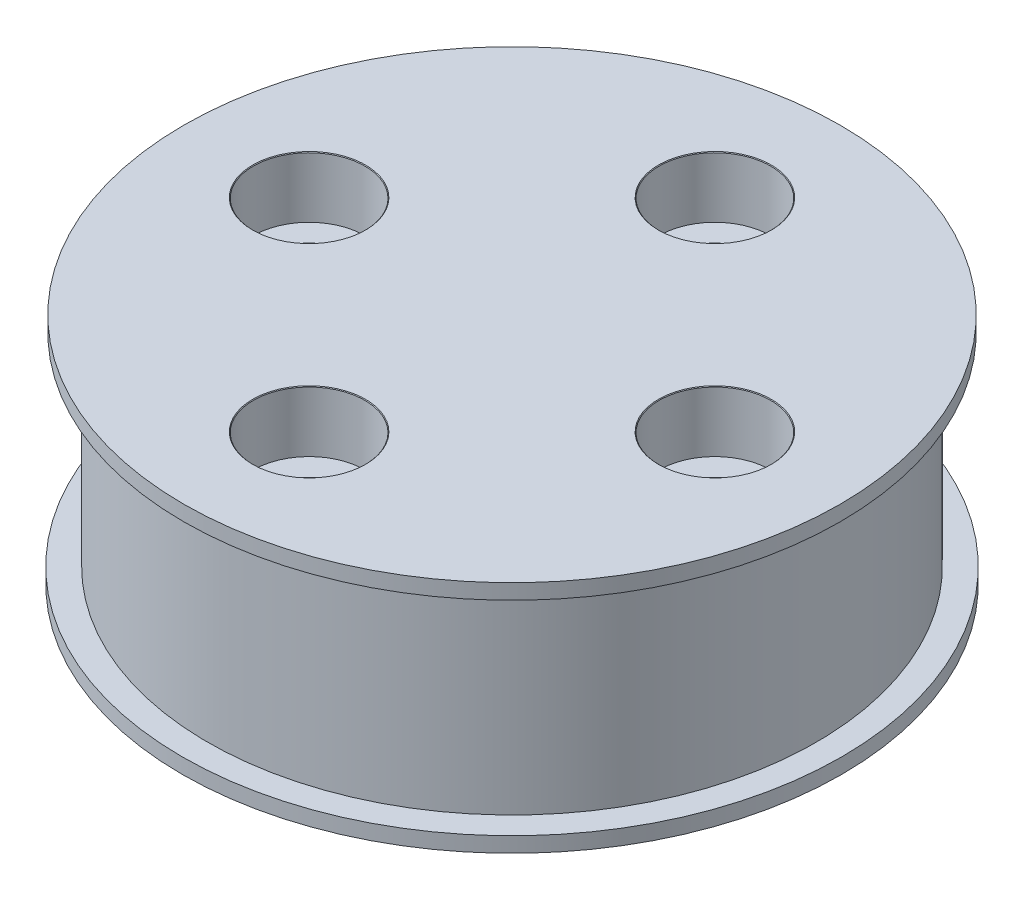
SolidWorks part; units mm, degrees
ref_plane "Front Plane" through (0, 0, 0) normal (0, 0, 1) x (1, 0, 0)
ref_plane "Top Plane" through (0, 0, 0) normal (0, 1, 0) x (1, 0, 0)
ref_plane "Right Plane" through (0, 0, 0) normal (1, 0, 0) x (0, 0, -1)
sketch "Sketch1" plane through (0, 0, 0) normal (0, 0, 1) x (1, 0, 0)
  line L0 (0, 0) -> (13, 0)
  line L1 (13, 0) -> (13, 0.6)
  line L2 (13, 0.6) -> (12, 0.6)
  line L3 (12, 0.6) -> (12, 8.6)
  line L4 (12, 8.6) -> (12.9429, 8.6)
  line L5 (12.9429, 8.6) -> (12.9429, 9.2)
  line L6 (12.9429, 9.2) -> (0, 9.2)
  line L7 (0, 9.2) -> (0, 0)
  dimension "D1" = 0.6
  dimension "D2" = 8
  dimension "D3" = 1
  dimension "D4" = 12
revolve "Revolve1" add sketch "Sketch1" angle 360 about L7
hole_wizard "CBORE for M2 Hex Socket Head Cap Screw1" positions "Sketch5" profile "Sketch3" counterbore size "M2" standard "DIN" end condition through all
sketch "Sketch5" plane through (0, 9.2, 0) normal (0, 1, 0) x (1, 0, 0)
  circle A0 centre (0, 0) radius 8
  point P4 (0, 8)
  point P10 (8, 0)
  point P11 (0, -8)
  point P12 (-8, 0)
  dimension "D1" = 16
  dimension "D2" = 4
sketch "Sketch3" plane through (-8, 9.2, 0) normal (1, 0, 0) x (0, 0, 1)
  line L0 (0, 0) -> (0, 9.2)
  line L1 (0, 9.2) -> (1.2, 9.2)
  line L3 (1.2, 9.2) -> (1.2, 2.4)
  line L4 (2.2, 2.4) -> (1.2, 2.4)
  line L5 (2.2, 2.4) -> (2.2, 0.025)
  line L6 (2.2, 0.025) -> (2.225, 0)
  line L7 (2.225, 0) -> (0, 0)
  line L8 (-2.2, 0.025) -> (-2.225, 0) construction
  line L11 (0, -6.35) -> (0, 107.95) construction
  dimension "Thru Hole Dia." = 2.4
  dimension "Thru Hole Depth" = 9.2
  dimension "C'Bore Dia." = 4.4
  dimension "C'Bore Depth" = 2.4
  dimension "Near C'Sink Dia." = 4.45
  dimension "Near C'Sink Angle" = 90
sketch "Sketch6" plane through (0, 0, 0) normal (0, -1, 0) x (1, 0, 0)
  circle A0 centre (0, 0) radius 4
  dimension "D1" = 8
extrude "Cut-Extrude1" cut sketch "Sketch6" against normal blind 2.5
